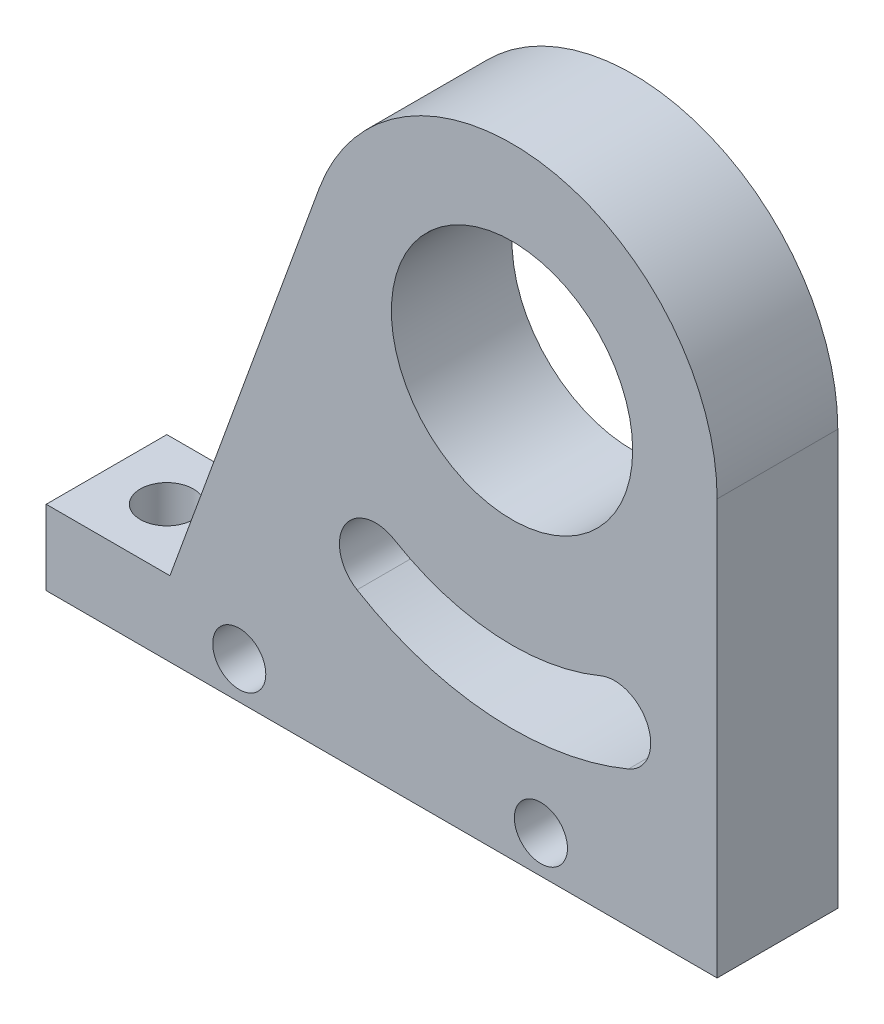
SolidWorks part; units mm, degrees
material "6061 Alloy"
ref_plane "Front Plane" through (0, 0, 0) normal (0, 0, 1) x (1, 0, 0)
ref_plane "Top Plane" through (0, 0, 0) normal (0, 1, 0) x (1, 0, 0)
ref_plane "Right Plane" through (0, 0, 0) normal (1, 0, 0) x (0, 0, -1)
sketch "Sketch1" plane through (0, 0, 0) normal (0, 0, 1) x (1, 0, 0)
  line L0 (-26.7836, -11.003) -> (22.5905, -28.9737) construction
  line L1 (0, 0) -> (17.7131, 0) construction
  line L2 (17, 0) -> (17, -34.3882)
  line L3 (-15.9748, 5.8143) -> (-30.6073, -34.3882)
  line L4 (17, -34.3882) -> (-30.6073, -34.3882)
  circle A0 centre (0, 0) radius 10
  arc A1 (-15.9748, 5.8143) -> (17, 0) centre (0, 0) cw
  dimension "D1" = 20
  dimension "D4" = 7
  dimension "D2" = 20
  dimension "D3" = 19.5
  dimension "D5" = 7
extrude "3/8" add sketch "Sketch1" along normal blind 10
sketch "Sketch2" plane through (0, 0, 0) normal (0, 0, 1) x (1, 0, 0)
  line L2 (12.2375, -26.8001) -> (12.2375, -16.8001) construction
  line L4 (-20.6657, -20.9984) -> (-17.2455, -11.6014) construction
  line L5 (-15.9748, 5.8143) -> (-30.6073, -34.3882) construction
  line L6 (17, 0) -> (17, -34.3882) construction
  circle A0 centre (12.2375, -26.8001) radius 2.2
  circle A1 centre (12.2375, -16.8001) radius 2.25
  circle A2 centre (-20.6657, -20.9984) radius 2.2
  circle A3 centre (-17.2455, -11.6014) radius 2.2
  arc A4 (-18.9556, -16.2999) -> (12.2375, -21.8001) centre (0, 0) ccw construction
  dimension "D3" = 4.4
  dimension "D6" = 4.4
  dimension "D7" = 25
  dimension "D1" = 4.7625
  dimension "D2" = 10
  dimension "D4" = 10
  dimension "D5" = 4.7625
sketch "Sketch4" plane through (0, 0, 10) normal (0, 0, 1) x (1, 0, 0)
  line L0 (-15.9748, 5.8143) -> (-30.6073, -34.3882) construction
  line L1 (17, -34.3882) -> (17, 0) construction
  arc A0 (-11.3041, -18.8737) -> (8.4913, -20.2953) centre (0, 0) ccw construction
  arc A1 (-9.7627, -16.3) -> (7.3334, -17.5277) centre (0, 0) ccw
  arc A2 (-12.8456, -21.4474) -> (9.6492, -23.0628) centre (0, 0) ccw
  arc A3 (-9.7627, -16.3) -> (-12.8456, -21.4474) centre (-11.3041, -18.8737) ccw
  arc A4 (7.3334, -17.5277) -> (9.6492, -23.0628) centre (8.4913, -20.2953) cw
  dimension "D1" = 22
  dimension "D2" = 6
  dimension "D3" = 3
  dimension "D4" = 12.8328
  dimension "D5" = 8.5087
extrude "Cut-Extrude2" cut sketch "Sketch4" against normal up to surface (10 mm away) up to face at (-2.5357, -12.2819, 0)
sketch "Sketch6" plane through (0, 0, 10) normal (0, 0, 1) x (1, 0, 0)
  line L0 (-30.6073, -34.3882) -> (-38.6073, -34.3882)
  line L1 (-38.6073, -34.3882) -> (-38.6073, -28.1882)
  line L2 (-38.6073, -28.1882) -> (-28.3507, -28.1882)
  line L3 (-15.9748, 5.8143) -> (-30.6073, -34.3882) construction
  line L4 (-28.3507, -28.1882) -> (-30.6073, -34.3882)
  dimension "D1" = 8
  dimension "D2" = 6.2
extrude "Boss-Extrude2" add sketch "Sketch6" against normal up to surface (10 mm away) up to face at (-1.4427, -20.0891, 0)
sketch "Sketch5" plane through (0, -34.3882, 0) normal (0, -1, 0) x (1, 0, 0)
  line L0 (-38.6073, 5) -> (17, 5) construction
  line L2 (17, 10) -> (17, 0) construction
  line L3 (-38.6073, 0) -> (-38.6073, 10) construction
  circle A0 centre (-33.6073, 5) radius 2.2
  circle A1 centre (-8.6073, 5) radius 2.2
  dimension "D1" = 4.4
  dimension "D2" = 4.4
  dimension "D3" = 5
  dimension "D4" = 25
extrude "M5_DRILL" cut sketch "Sketch5" against normal blind 8
sketch "Sketch7" plane through (0, 0, 10) normal (0, 0, 1) x (1, 0, 0)
  line L0 (-38.6073, -31.2882) -> (-22.6073, -31.2882) construction
  line L1 (-38.6073, -28.1882) -> (-38.6073, -34.3882) construction
  circle A0 centre (-22.6073, -31.2882) radius 2.2
  circle A1 centre (2.3927, -31.2882) radius 2.2
  dimension "D1" = 4.4
  dimension "D3" = 2
  dimension "D2" = 16
extrude "M4_through2" cut sketch "Sketch7" against normal up to surface (10 mm away) up to face at (-1.4427, -20.0891, 0)
